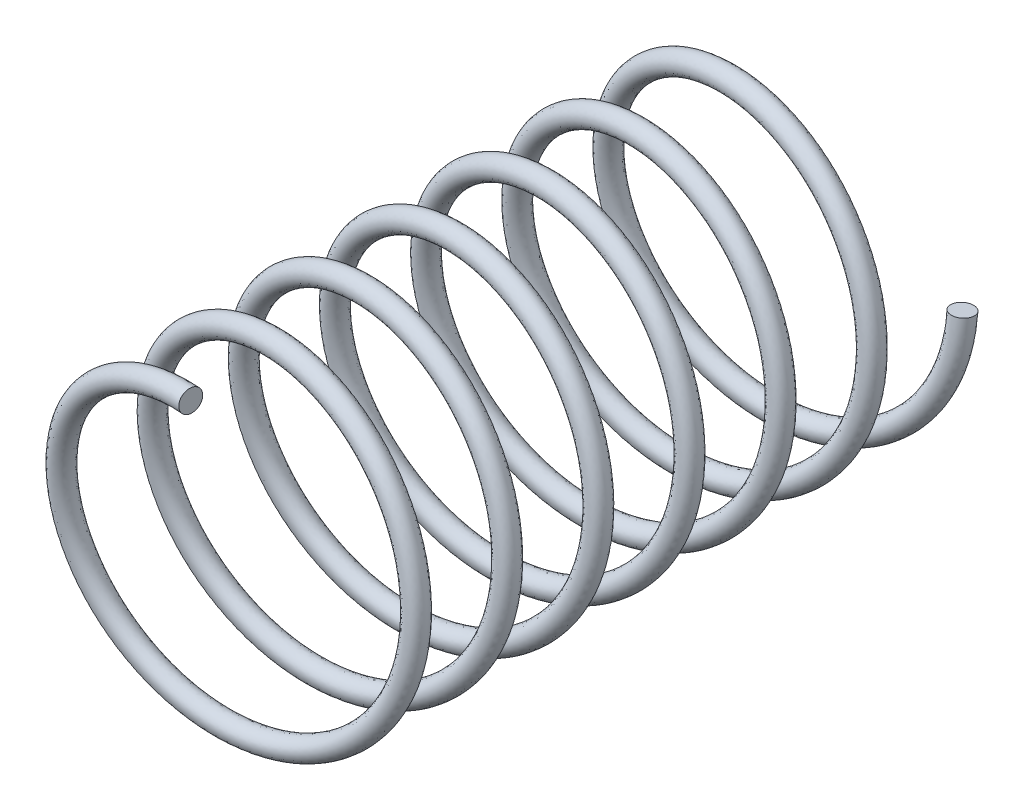
SolidWorks part; units mm, degrees
material "AISI 1020"
ref_plane "Front" through (0, 0, 0) normal (0, 0, 1) x (1, 0, 0)
ref_plane "Top" through (0, 0, 0) normal (0, 1, 0) x (1, 0, 0)
ref_plane "Right" through (0, 0, 0) normal (1, 0, 0) x (0, 0, -1)
sketch "Sketch1" plane through (0, 0, 0) normal (0, 0, 1) x (1, 0, 0)
  circle A0 centre (0, 0) radius 7
curve "Helix/Spiral1" pitch 4.1481 height 28 turns 6.75
sweep "Sweep1" add path "Helix/Spiral1" circular profile diameter 1 parameters "D3"=1
